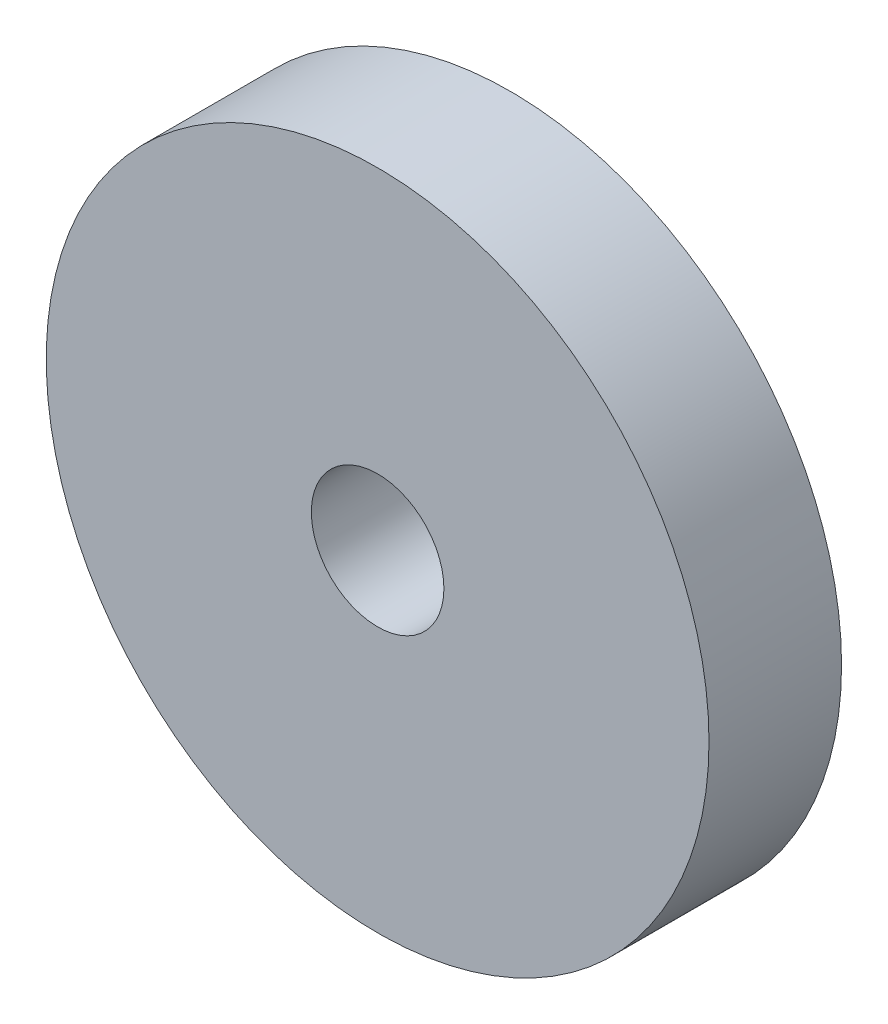
SolidWorks part; units mm, degrees
material "POM 乙缩醛共聚物"
ref_plane "前视基准面" through (0, 0, 0) normal (0, 0, 1) x (1, 0, 0)
ref_plane "上视基准面" through (0, 0, 0) normal (0, 1, 0) x (1, 0, 0)
ref_plane "右视基准面" through (0, 0, 0) normal (1, 0, 0) x (0, 0, -1)
sketch "草图1" plane through (0, 0, 0) normal (0, 0, 1) x (1, 0, 0)
  circle A0 centre (0, 0) radius 15
  circle A1 centre (0, 0) radius 3
  dimension "D1" = 30
  dimension "D2" = 6
extrude "凸台-拉伸1" add sketch "草图1" along normal blind 6
